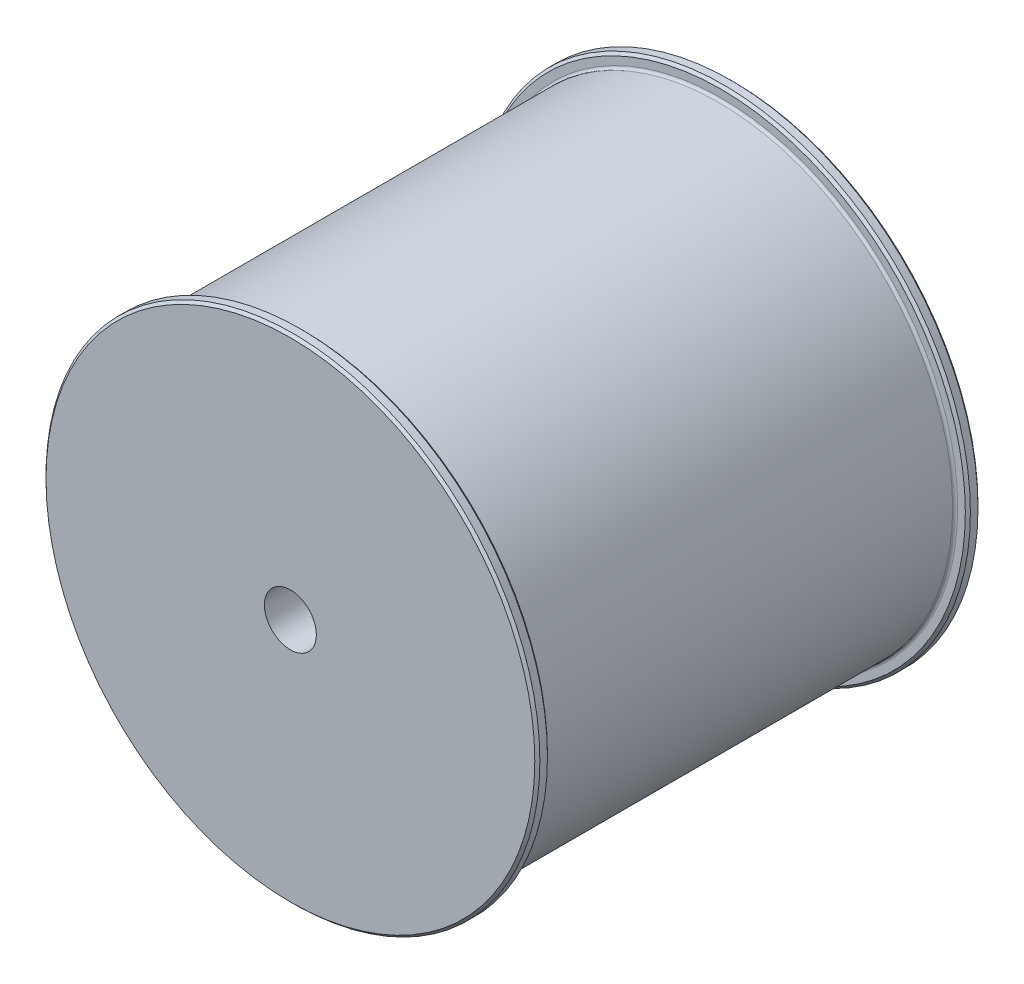
SolidWorks part; units mm, degrees
material "AW 6082"
ref_plane "Front Plane" through (0, 0, 0) normal (0, 0, 1) x (1, 0, 0)
ref_plane "Top Plane" through (0, 0, 0) normal (0, 1, 0) x (1, 0, 0)
ref_plane "Right Plane" through (0, 0, 0) normal (1, 0, 0) x (0, 0, -1)
sketch "Sketch1" plane through (0, 0, 0) normal (0, 0, 1) x (1, 0, 0)
  circle A0 centre (0, 0) radius 19.5
  dimension "D1" = 39
extrude "Boss-Extrude1" add sketch "Sketch1" along normal blind 1
sketch "Sketch2" plane through (0, 0, 1) normal (0, 0, 1) x (1, 0, 0)
  circle A0 centre (0, 0) radius 18.5
  dimension "D1" = 37
extrude "Boss-Extrude2" add sketch "Sketch2" along normal blind 33
sketch "Sketch3" plane through (0, 0, 34) normal (0, 0, 1) x (1, 0, 0)
  circle A0 centre (0, 0) radius 19.5
  dimension "D1" = 39
extrude "Boss-Extrude3" add sketch "Sketch3" along normal blind 1
fillet "Fillet1" radius 0.2 2 edges at (18.5, 0, 1) (18.5, 0, 34)
chamfer "Chamfer1" distance 0.2 angle 45 4 edges at (19.5, 0, 34) (19.5, 0, 35) (19.5, 0, 0) (19.5, 0, 1)
sketch "Sketch4" plane through (0, 0, 35) normal (0, 0, 1) x (1, 0, 0)
  circle A0 centre (0, 0) radius 2.05
  dimension "D1" = 4.1
extrude "Cut-Extrude1" cut sketch "Sketch4" against normal through all
